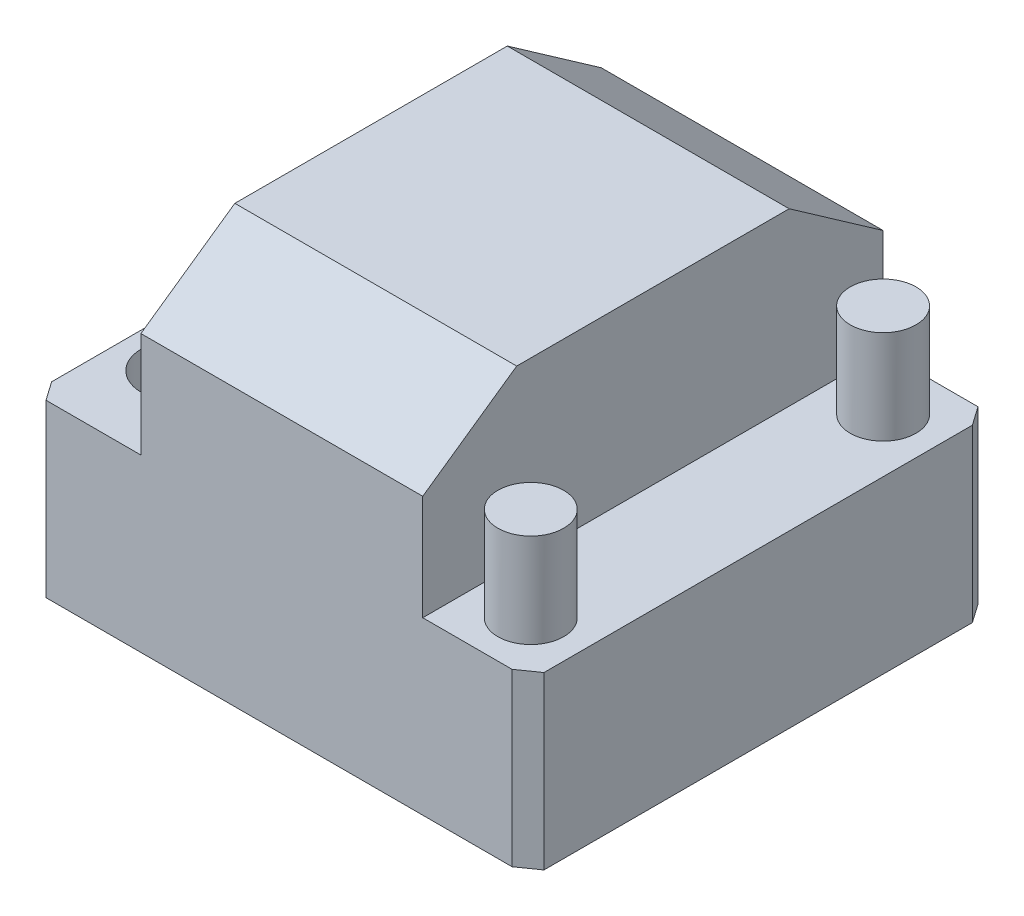
SolidWorks part; units mm, degrees
ref_plane "Front Plane" through (0, 0, 0) normal (0, 0, 1) x (1, 0, 0)
ref_plane "Top Plane" through (0, 0, 0) normal (0, 1, 0) x (1, 0, 0)
ref_plane "Right Plane" through (0, 0, 0) normal (1, 0, 0) x (0, 0, -1)
sketch "Sketch2" plane through (0, 0, 0) normal (0, 1, 0) x (1, 0, 0)
  line L1 (0, 0) -> (53, 0)
  line L2 (0, 0) -> (0, -49)
  line L3 (0, -49) -> (53, -49)
  line L4 (53, 0) -> (53, -49)
  point P4 (0, 0)
  dimension "D1" = 53
  dimension "D2" = 49
extrude "Boss-Extrude1" add sketch "Sketch2" along normal blind 36.4
sketch "Sketch3" plane through (0, 0, 49) normal (0, 0, 1) x (1, 0, 0)
  line L0 (0, 36.4) -> (0, 0) construction
  line L1 (0, 36.4) -> (11.5, 36.4)
  line L2 (0, 36.4) -> (0, 18.2)
  line L3 (0, 18.2) -> (11.5, 18.2)
  line L4 (11.5, 36.4) -> (11.5, 18.2)
  line L6 (53, 36.4) -> (41.5, 36.4)
  line L7 (53, 36.4) -> (53, 18.2)
  line L8 (53, 18.2) -> (41.5, 18.2)
  line L9 (41.5, 36.4) -> (41.5, 18.2)
  dimension "D1" = 30
extrude "Cut-Extrude1" cut sketch "Sketch3" against normal through all
chamfer "Chamfer1" distance 10 angle 35 2 edges at (26.5, 36.4, 0) (26.5, 36.4, 49)
chamfer "Chamfer2" distance 2 angle 35 4 edges at (53, 9.1, 0) (53, 9.1, 49) (0, 9.1, 0) (0, 9.1, 49)
sketch "Sketch4" plane through (0, 18.2, 0) normal (0, 1, 0) x (1, 0, 0)
  line L0 (41.5, 0) -> (51.5996, 0) construction
  line L1 (53, -2) -> (53, -47.5996) construction
  line L2 (41.5, -10) -> (41.5, -39) construction
  line L3 (41.5, -49) -> (51, -49) construction
  circle A0 centre (47.25, -43.25) radius 5.75 construction
  circle A1 centre (47.25, -5.75) radius 5.75 construction
  circle A2 centre (47.25, -43.25) radius 3.5
  circle A3 centre (47.25, -5.75) radius 3.5
  dimension "D1" = 7
extrude "Boss-Extrude2" add sketch "Sketch4" along normal blind 10
sketch "Sketch5" plane through (0, 18.2, 0) normal (0, 1, 0) x (1, 0, 0)
  line L0 (0, -24.2002) -> (5.75, -24.2002) construction
  line L1 (0, -1.4004) -> (0, -47) construction
  line L2 (5.75, -9.2002) -> (5.75, -39.2002) construction
  line L3 (11.5, 0) -> (11.5, -49) construction
  circle A0 centre (5.75, -24.2002) radius 5.75 construction
  circle A1 centre (5.75, -9.2002) radius 4
  circle A2 centre (5.75, -39.2002) radius 4
  circle A3 centre (5.75, -24.2002) radius 4
  dimension "D2" = 8
  dimension "D1" = 30
extrude "Cut-Extrude2" cut sketch "Sketch5" against normal blind 10
